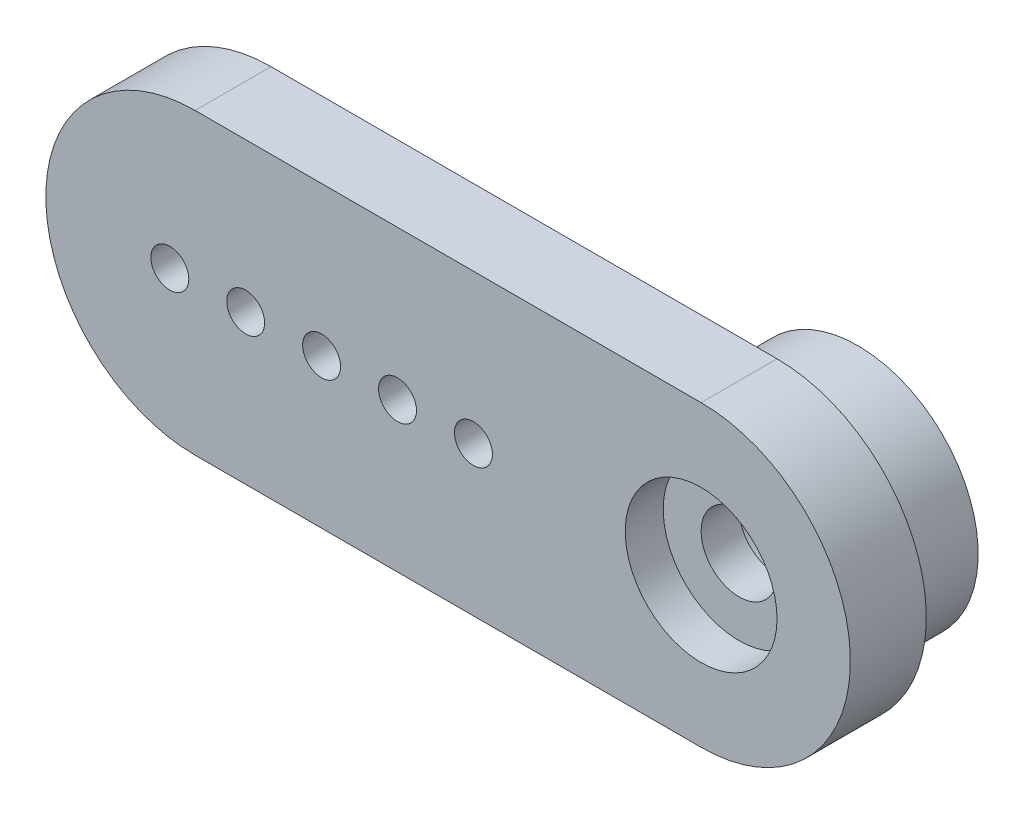
SolidWorks part; units mm, degrees
material "ABS"
ref_plane "Front" through (0, 0, 0) normal (0, 0, 1) x (1, 0, 0)
ref_plane "Top" through (0, 0, 0) normal (0, 1, 0) x (1, 0, 0)
ref_plane "Right" through (0, 0, 0) normal (1, 0, 0) x (0, 0, -1)
sketch "Esquisse1" plane through (0, 0, 0) normal (0, 0, 1) x (1, 0, 0)
  line L0 (-21, 0) -> (-18, 0) construction
  line L1 (0, 0) -> (-20, 0) construction
  line L2 (0, -5.9) -> (-20, -5.9)
  line L3 (0, 5.9) -> (-20, 5.9)
  circle A0 centre (0, 0) radius 3
  circle A1 centre (-21, 0) radius 0.75
  circle A2 centre (-18, 0) radius 0.75
  circle A3 centre (-15, 0) radius 0.75
  circle A4 centre (-12, 0) radius 0.75
  circle A5 centre (-9, 0) radius 0.75
  arc A6 (0, -5.9) -> (0, 5.9) centre (0, 0) ccw
  arc A7 (-20, 5.9) -> (-20, -5.9) centre (-20, 0) ccw
  point P5 (-10, 0)
  dimension "D1" = 5
  dimension "D3" = 1.5
  dimension "D4" = 6
  dimension "D5" = 21
  dimension "D7" = 31.8
  dimension "D2" = 3
  dimension "D6" = 11.8
extrude "Boss.-Extru.1" add sketch "Esquisse1" against normal blind 3
sketch "Esquisse2" plane through (0, 0, 0) normal (0, 1, 0) x (1, 0, 0)
  line L0 (0, 6.2) -> (0, 0) construction
  line L1 (-4.75, 6.2) -> (-2.75, 6.2)
  line L2 (-4.75, 6.2) -> (-4.75, 1.5)
  line L3 (-4.75, 1.5) -> (-1.5, 1.5)
  line L4 (-1.5, 3) -> (-1.5, 1.5)
  line L7 (-1.5, 3) -> (-2.75, 3)
  line L8 (-2.75, 6.2) -> (-2.75, 3)
  line L9 (0, 0) -> (-20, 0) construction
  line L10 (0, 3) -> (-20, 3) construction
  point P7 (-1.5, 3.843)
  dimension "D1" = 6.2
  dimension "D2" = 1.5
  dimension "D3" = 9.5
  dimension "D4" = 5.5
  dimension "D5" = 3
revolve "Révolution1" add sketch "Esquisse2" angle 360 about L0
